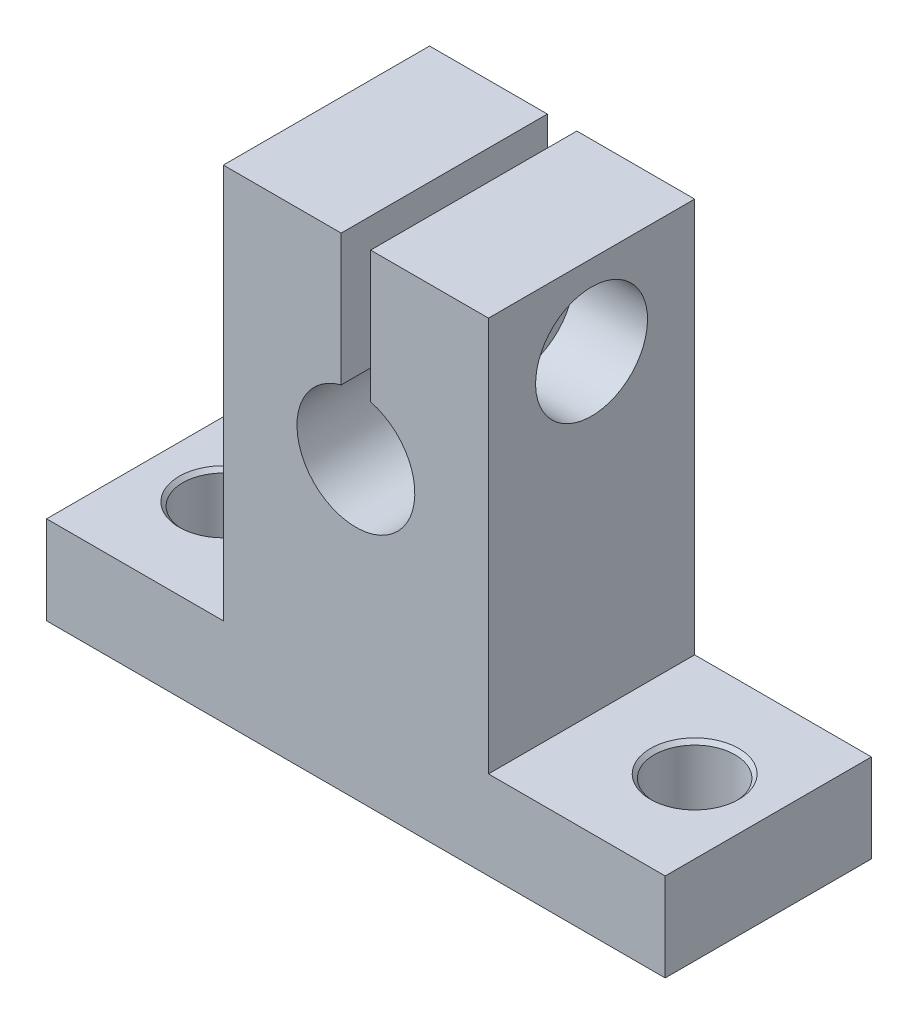
SolidWorks part; units mm, degrees
material "Д16Т ГОСТ 4784-97"
ref_plane "Спереди" through (0, 0, 0) normal (0, 0, 1) x (1, 0, 0)
ref_plane "Сверху" through (0, 0, 0) normal (0, 1, 0) x (1, 0, 0)
ref_plane "Справа" through (0, 0, 0) normal (1, 0, 0) x (0, 0, -1)
sketch "Эскиз1" plane through (0, 0, 0) normal (0, 0, 1) x (1, 0, 0)
  line L0 (-9, 16.4) -> (-1, 16.4)
  line L1 (-1, 16.4) -> (-1, 7.473)
  line L2 (1, 7.473) -> (1, 16.4)
  line L3 (1, 16.4) -> (9, 16.4)
  line L4 (9, 16.4) -> (9, -10.4)
  line L5 (9, -10.4) -> (21, -10.4)
  line L6 (21, -10.4) -> (21, -16.4)
  line L7 (21, -16.4) -> (-21, -16.4)
  line L8 (-21, -16.4) -> (-21, -10.4)
  line L9 (-21, -10.4) -> (-9, -10.4)
  line L10 (-9, -10.4) -> (-9, 16.4)
  line L11 (-1, 16.4) -> (1, 16.4) construction
  line L12 (0, 16.4) -> (0, -16.4) construction
  arc A0 (-1, 7.473) -> (1, 7.473) centre (0, 3.6) ccw
  dimension "D2" = 20
  dimension "D" = 8
  dimension "D1" = 2
  dimension "E" = 18
  dimension "H" = 32.8
  dimension "G" = 6
  dimension "W" = 42
extrude "Бобышка-Вытянуть1" add sketch "Эскиз1" along normal mid plane 14
sketch "Эскиз2" plane through (0, -10.4, 0) normal (0, 1, 0) x (1, 0, 0)
  line L0 (-16, 0) -> (16, 0) construction
  circle A0 centre (-16, 0) radius 2.75
  circle A1 centre (16, 0) radius 2.75
  dimension "S" = 5.5
  dimension "C" = 32
extrude "Вырез-Вытянуть1" cut sketch "Эскиз2" against normal up to surface (6 mm away) up to face at (0, -16.4, 0)
sketch "Эскиз4" plane through (-1, 0, 0) normal (1, 0, 0) x (0, 0, -1)
  line L0 (-7, 11.9365) -> (7, 11.9365) construction
  line L2 (-7, 7.473) -> (-7, 16.4) construction
  line L3 (7, 7.473) -> (7, 16.4) construction
  circle A0 centre (0, 10.9365) radius 1.65
  dimension "D1" = 1
  dimension "dM" = 3.3
extrude "Вырез-Вытянуть2" cut sketch "Эскиз4" against normal up to surface (8 mm away) up to face at (-9, 3, 0)
cosmetic thread "Условное изображение резьбы1" parameters "D2"=4
sketch "Эскиз5" plane through (9, 0, 0) normal (1, 0, 0) x (0, 0, -1)
  circle A0 centre (0, 10.9365) radius 2.1
  dimension "dM1" = 4.2
extrude "Вырез-Вытянуть3" cut sketch "Эскиз5" against normal up to surface (8 mm away) up to face at (1, 11.9365, 0)
sketch "Эскиз6" plane through (9, 0, 0) normal (1, 0, 0) x (0, 0, -1)
  circle A0 centre (0, 10.9365) radius 3.8
  dimension "dV" = 7.6
extrude "Вырез-Вытянуть4" cut sketch "Эскиз6" against normal blind 5
chamfer "Фаска1" distance 0.25 angle 45 3 edges at (13.25, -10.4, 0) (-18.75, -10.4, 0) (-9, 12.5865, 0)
